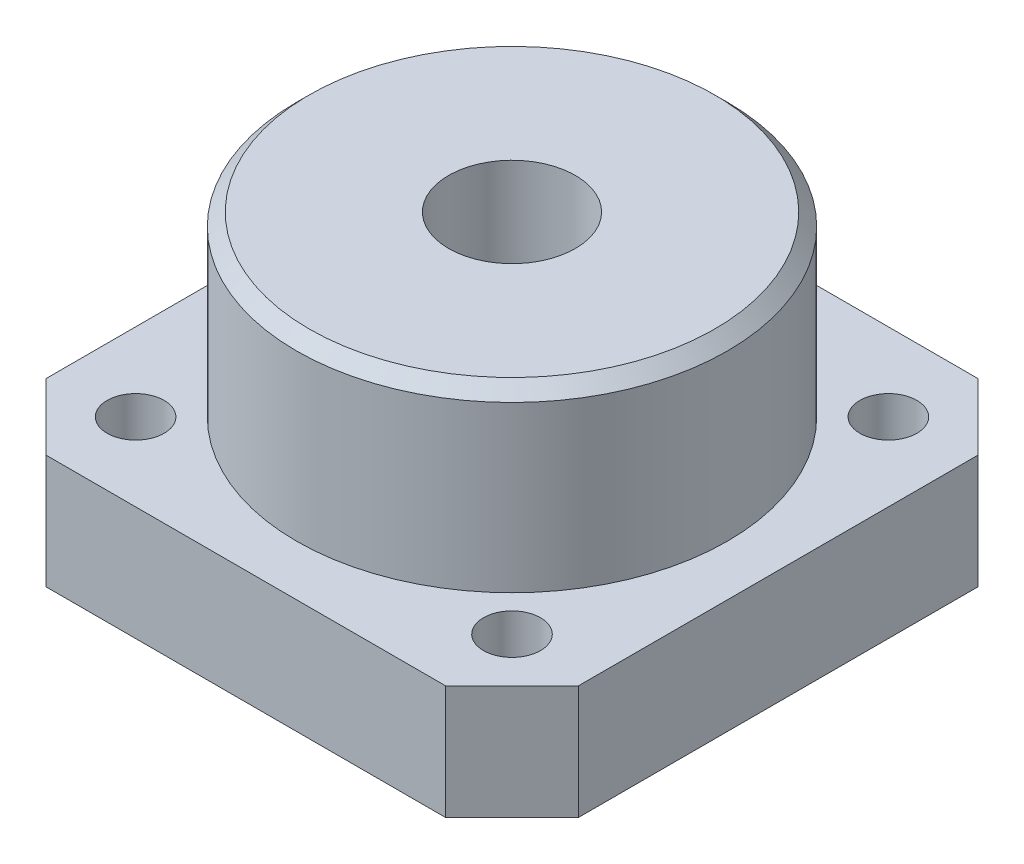
SolidWorks part; units mm, degrees
ref_plane "Front" through (0, 0, 0) normal (0, 0, 1) x (1, 0, 0)
ref_plane "Top" through (0, 0, 0) normal (0, 1, 0) x (1, 0, 0)
ref_plane "Right" through (0, 0, 0) normal (1, 0, 0) x (0, 0, -1)
sketch "草图1" plane through (0, 0, 0) normal (0, 1, 0) x (1, 0, 0)
  line L0 (-37.0982, 0) -> (38.5722, 0) construction
  line L1 (0, 35.9274) -> (0, -37.45) construction
  line L2 (0, 21) -> (15.7696, 21)
  line L3 (15.7696, 21) -> (21, 15.7696)
  line L4 (21, 15.7696) -> (21, 0)
  line L5 (0, 0) -> (24.6032, 24.6032) construction
  line L6 (21, 0) -> (21, -15.7696)
  line L7 (21, -15.7696) -> (15.7696, -21)
  line L8 (15.7696, -21) -> (0, -21)
  line L9 (0, -21) -> (-15.7696, -21)
  line L10 (-15.7696, -21) -> (-21, -15.7696)
  line L11 (-21, -15.7696) -> (-21, 0)
  line L12 (-21, 0) -> (-21, 15.7696)
  line L13 (-21, 15.7696) -> (-15.7696, 21)
  line L14 (-15.7696, 21) -> (0, 21)
  circle A0 centre (14.8492, 14.8492) radius 2.25
  circle A1 centre (14.8492, -14.8492) radius 2.25
  circle A2 centre (-14.8492, -14.8492) radius 2.25
  circle A3 centre (-14.8492, 14.8492) radius 2.25
  point P34 (0, 0)
  dimension "D5" = 4.5
  dimension "D1" = 21
  dimension "D2" = 42
  dimension "D3" = 26
  dimension "D4" = 135
  dimension "D6" = 21
  dimension "D7" = 4
extrude "凸台-拉伸1" add sketch "草图1" along normal blind 9
sketch "草图2" plane through (0, 0, 0) normal (0, 1, 0) x (1, 0, 0)
  circle A0 centre (-14.8492, 14.8492) radius 4
  circle A1 centre (14.8492, 14.8492) radius 4
  circle A2 centre (14.8492, -14.8492) radius 4
  circle A3 centre (-14.8492, -14.8492) radius 4
  point P3 (0, 0)
  point P4 (0, 0)
  point P12 (0, 0)
  dimension "D1" = 8
  dimension "D2" = 4
extrude "切除-拉伸1" cut sketch "草图2" along normal blind 4
sketch "草图3" plane through (0, 9, 0) normal (0, 1, 0) x (1, 0, 0)
  circle A0 centre (0, 0) radius 17
  dimension "D1" = 34
extrude "凸台-拉伸2" add sketch "草图3" along normal blind 14
sketch "草图4" plane through (0, 0, 0) normal (0, -1, 0) x (1, 0, 0)
  circle A0 centre (0, 0) radius 13
  circle A1 centre (0, 0) radius 11
  dimension "D1" = 26
  dimension "D2" = 2
extrude "凸台-拉伸3" add sketch "草图4" along normal blind 7.5
sketch "草图5" plane through (0, 23, 0) normal (0, 1, 0) x (1, 0, 0)
  circle A0 centre (0, 0) radius 5
  dimension "D1" = 10
extrude "切除-拉伸2" cut sketch "草图5" against normal up to next
chamfer "倒角1" distance 1 angle 45 2 edges at (0, -7.5, -13) (0, 23, 17)
